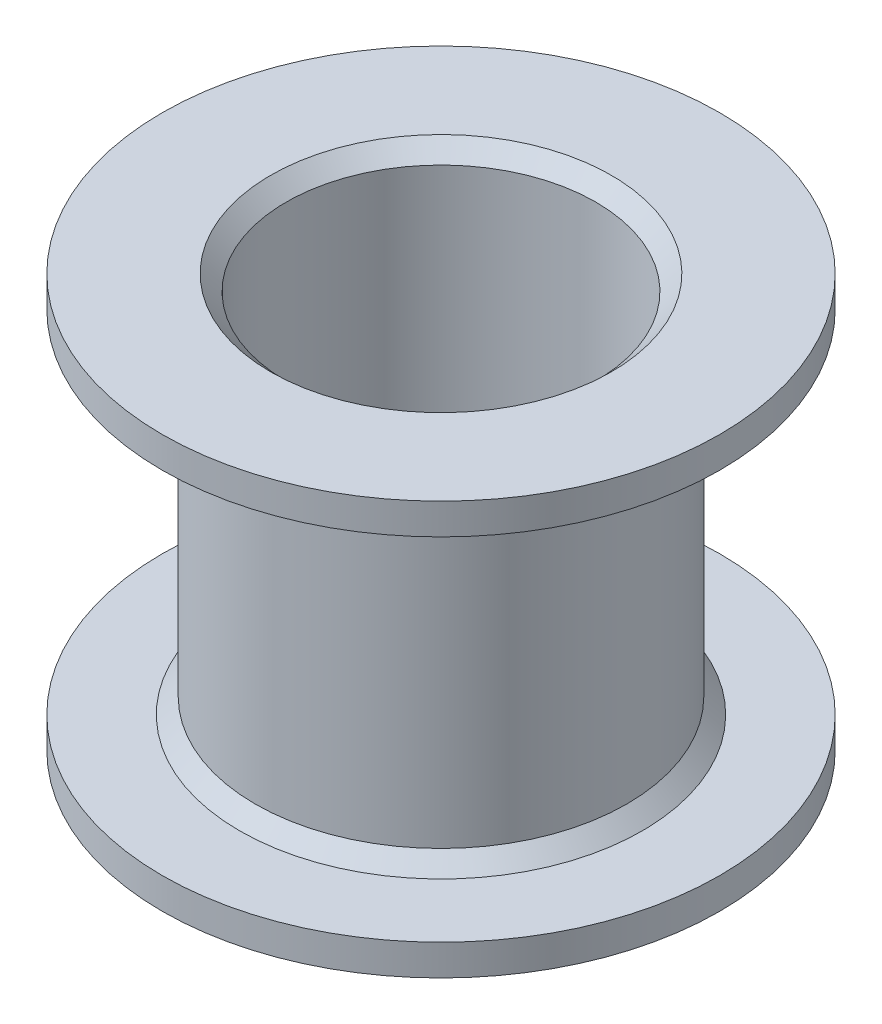
SolidWorks part; units mm, degrees
material "Custom Stainless Steel 1"
ref_plane "Front Plane" through (0, 0, 0) normal (0, 0, 1) x (1, 0, 0)
ref_plane "Top Plane" through (0, 0, 0) normal (0, 1, 0) x (1, 0, 0)
ref_plane "Right Plane" through (0, 0, 0) normal (1, 0, 0) x (0, 0, -1)
sketch "Sketch1" plane through (0, 0, 0) normal (0, 1, 0) x (1, 0, 0)
  circle A0 centre (0, 0) radius 1.8
  circle A1 centre (0, 0) radius 1.8 construction
  circle A2 centre (0, 0) radius 1.5
  circle A3 centre (0, 0) radius 1.5 construction
extrude "Boss-Extrude1" add sketch "Sketch1" along normal blind 1.7
sketch "Sketch2" plane through (0, 1.7, 0) normal (0, 1, 0) x (1, 0, 0)
  circle A0 centre (0, 0) radius 1.5
  circle A1 centre (0, 0) radius 1.5 construction
  circle A2 centre (0, 0) radius 2.7
  circle A3 centre (0, 0) radius 2.7 construction
extrude "Boss-Extrude2" add sketch "Sketch2" along normal blind 0.3
chamfer "Chamfer1" distance 0.15 angle 45 1 edges at (0, 1.7, 1.8)
chamfer "Chamfer2" distance 0.15 angle 45 1 edges at (0, 2, 1.5)
mirror "Mirror1" about plane through (0, 0, 0) normal (0, 1, 0) of bodies 102
sketch3d "3DSketch1"
  line L0 (0, 2, 0) -> (0, -2, 0) construction
